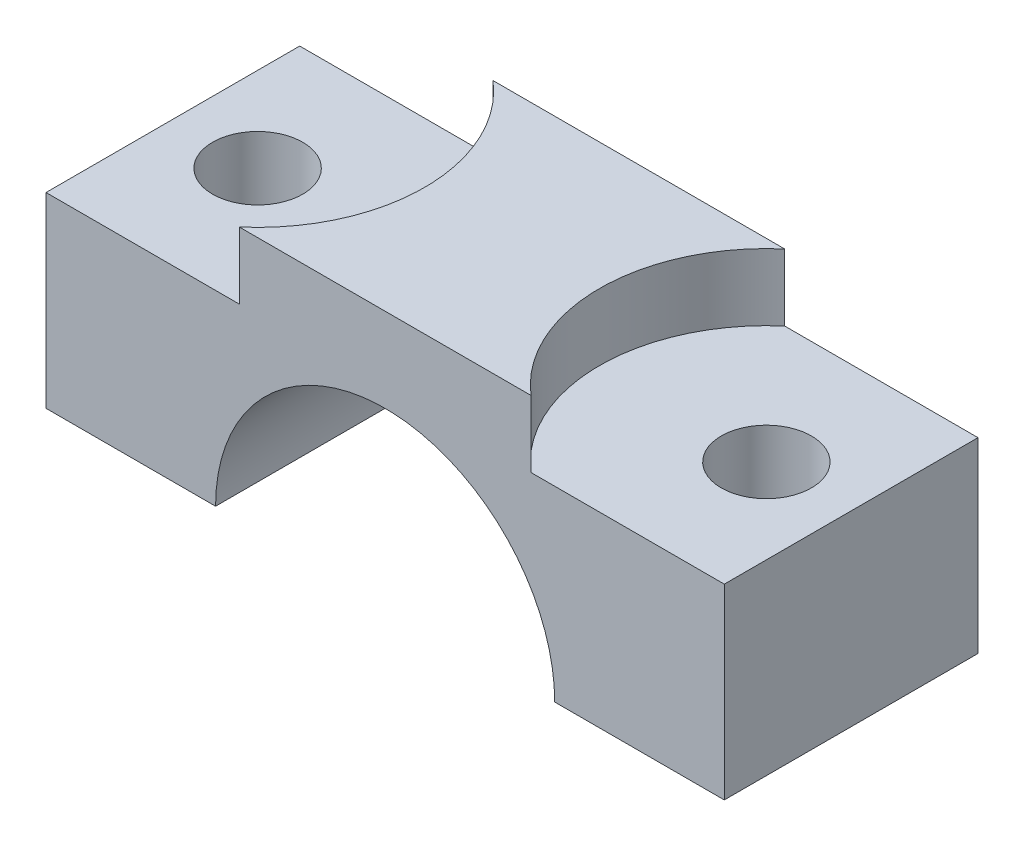
SolidWorks part; units mm, degrees
ref_plane "Front Plane" through (0, 0, 0) normal (0, 0, 1) x (1, 0, 0)
ref_plane "Top Plane" through (0, 0, 0) normal (0, 1, 0) x (1, 0, 0)
ref_plane "Right Plane" through (0, 0, 0) normal (1, 0, 0) x (0, 0, -1)
sketch "Sketch1" plane through (0, 0, 0) normal (0, 0, 1) x (1, 0, 0)
  line L0 (-25.4, 0) -> (-25.4, 19)
  line L1 (-25.4, 19) -> (25.4, 19)
  line L2 (25.4, 19) -> (25.4, 0)
  line L3 (-25.4, 0) -> (-12.7, 0)
  line L4 (12.7, 0) -> (25.4, 0)
  arc A0 (-12.7, 0) -> (12.7, 0) centre (0, 0) cw
  dimension "D3" = 12.7
  dimension "D1" = 50.8
  dimension "D2" = 19
extrude "Boss-Extrude1" add sketch "Sketch1" along normal mid plane 19
sketch "Sketch2" plane through (0, 0, 0) normal (0, -1, 0) x (1, 0, 0)
  line L0 (-19.05, 9.5) -> (-19.05, -9.5) construction
  line L1 (-25.4, 9.5) -> (-12.7, 9.5) construction
  line L2 (-25.4, -9.5) -> (-12.7, -9.5) construction
  line L3 (19.05, 9.5) -> (19.05, -9.5) construction
  line L4 (12.7, 9.5) -> (25.4, 9.5) construction
  line L5 (12.7, -9.5) -> (25.4, -9.5) construction
  point P12 (-19.05, 0)
  point P13 (19.05, 0)
sketch "Sketch3" plane through (0, 19, 0) normal (0, 1, 0) x (1, 0, 0)
  circle A0 centre (-19.05, 0) radius 12.5
  circle A1 centre (19.05, 0) radius 12.5
  dimension "D1" = 25
extrude "Cut-Extrude1" cut sketch "Sketch3" against normal blind 5
sketch "Sketch4" plane through (0, 14, 0) normal (0, 1, 0) x (1, 0, 0)
  line L0 (19.05, -9.5) -> (19.05, 9.5) construction
  circle A0 centre (-19.05, 0) radius 3.375
  circle A1 centre (19.05, 0) radius 3.375
  dimension "D1" = 6.75
extrude "Cut-Extrude2" cut sketch "Sketch4" against normal through all
